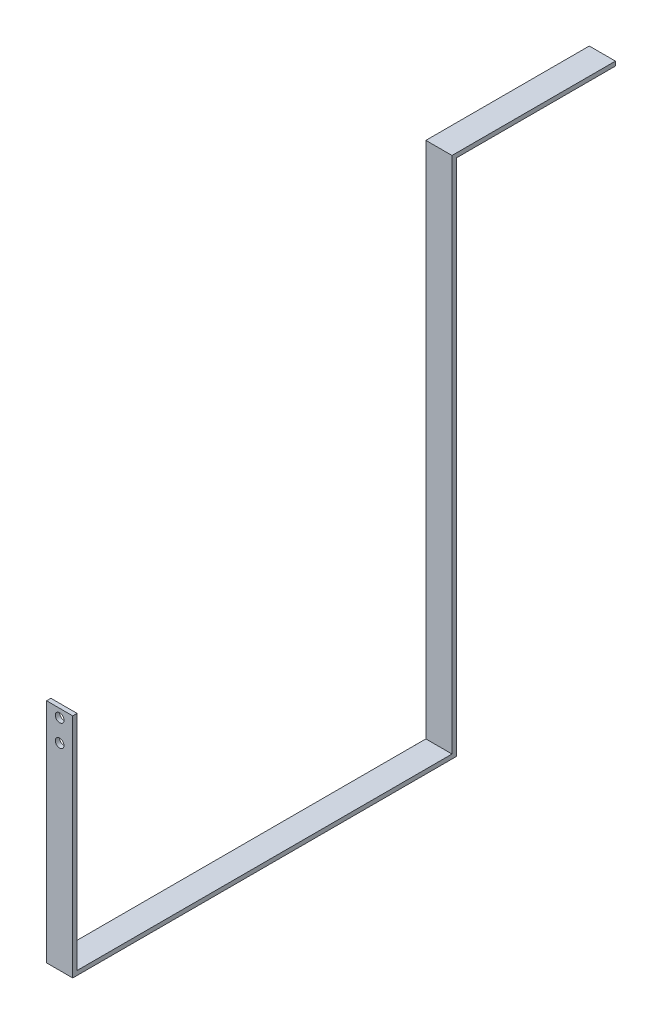
SolidWorks part; units mm, degrees
ref_plane "Alzado" through (0, 0, 0) normal (0, 0, 1) x (1, 0, 0)
ref_plane "Planta" through (0, 0, 0) normal (0, 1, 0) x (1, 0, 0)
ref_plane "Vista lateral" through (0, 0, 0) normal (1, 0, 0) x (0, 0, -1)
sketch "Croquis1" plane through (0, 0, 0) normal (0, 0, 1) x (1, 0, 0)
  line L1 (-19.05, -3.155) -> (19.05, -3.155)
  line L2 (-19.05, -3.155) -> (-19.05, 3.155)
  line L3 (-19.05, 3.155) -> (19.05, 3.155)
  line L4 (19.05, -3.155) -> (19.05, 3.155)
  line L5 (-19.05, -3.155) -> (19.05, 3.155) construction
  line L6 (-19.05, 3.155) -> (19.05, -3.155) construction
  point P0 (0, 0)
  dimension "D1" = 6.31
  dimension "D2" = 38.1
extrude "Saliente-Extruir1" add sketch "Croquis1" along normal blind 238.05
sketch "Croquis2" plane through (0, -3.155, 0) normal (0, -1, 0) x (1, 0, 0)
  line L0 (-19.05, 238.05) -> (19.05, 238.05)
  line L1 (19.05, 238.05) -> (19.05, 231.74)
  line L2 (19.05, 238.05) -> (19.05, 0) construction
  line L3 (19.05, 231.74) -> (-19.05, 231.74)
  line L4 (-19.05, 238.05) -> (-19.05, 0) construction
  line L5 (-19.05, 231.74) -> (-19.05, 238.05)
  dimension "D1" = 6.31
extrude "Saliente-Extruir2" add sketch "Croquis2" along normal blind 755.1
sketch "Croquis3" plane through (0, 0, 238.05) normal (0, 0, 1) x (1, 0, 0)
  line L0 (-19.05, -758.255) -> (19.05, -758.255)
  line L1 (19.05, -758.255) -> (19.05, -751.945)
  line L2 (19.05, -758.255) -> (19.05, 3.155) construction
  line L3 (19.05, -751.945) -> (-19.05, -751.945)
  line L4 (-19.05, 3.155) -> (-19.05, -758.255) construction
  line L5 (-19.05, -751.945) -> (-19.05, -758.255)
  dimension "D1" = 6.31
extrude "Saliente-Extruir3" add sketch "Croquis3" along normal blind 552.5
sketch "Croquis4" plane through (0, -751.945, 0) normal (0, 1, 0) x (1, 0, 0)
  line L0 (-19.05, -790.55) -> (19.05, -790.55)
  line L1 (19.05, -790.55) -> (19.05, -784.24)
  line L2 (19.05, -790.55) -> (19.05, -238.05) construction
  line L3 (19.05, -784.24) -> (-19.05, -784.24)
  line L4 (-19.05, -790.55) -> (-19.05, -238.05) construction
  line L5 (-19.05, -784.24) -> (-19.05, -790.55)
  dimension "D1" = 6.31
extrude "Saliente-Extruir4" add sketch "Croquis4" along normal blind 314.39
sketch "Croquis5" plane through (0, 0, 790.55) normal (0, 0, 1) x (1, 0, 0)
  line L0 (0, -383.4472) -> (0, -437.555) construction
  line L1 (-19.05, -437.555) -> (19.05, -437.555) construction
  line L2 (0, -383.4472) -> (0, -415.4472) construction
  line L3 (0, -415.4472) -> (21.1091, -415.4472) construction
  circle A0 centre (0, -383.4472) radius 6.35
  circle A1 centre (0, -415.4472) radius 6.35
sketch "Croquis6" plane through (0, -437.555, 0) normal (0, 1, 0) x (1, 0, 0)
  line L0 (19.05, -790.55) -> (-19.05, -790.55)
  line L1 (-19.05, -790.55) -> (-19.05, -784.24)
  line L2 (-19.05, -784.24) -> (19.05, -784.24)
  line L3 (19.05, -784.24) -> (19.05, -790.55)
extrude "Saliente-Extruir5" add sketch "Croquis6" along normal blind 10
sketch "Croquis8" plane through (0, 0, 790.55) normal (0, 0, 1) x (1, 0, 0)
  line L0 (-210, -471.4472) -> (0, -471.4472) construction
  line L1 (0, -471.4472) -> (0, -439.4472) construction
  circle A0 centre (0, -471.4472) radius 6.35
  circle A1 centre (0, -439.4472) radius 6.35
extrude "Cortar-Extruir1" cut sketch "Croquis8" against normal blind 10
